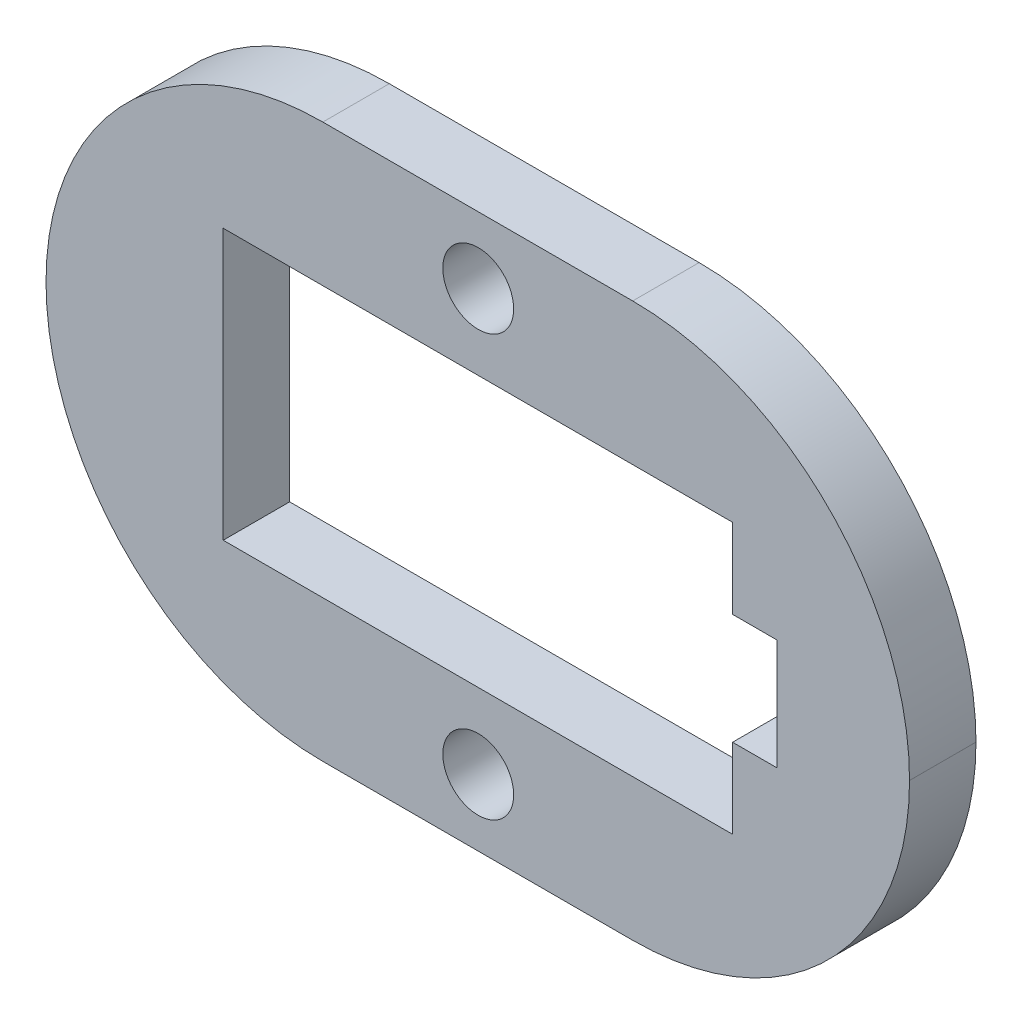
SolidWorks part; units mm, degrees
ref_plane "前视基准面" through (0, 0, 0) normal (0, 0, 1) x (1, 0, 0)
ref_plane "上视基准面" through (0, 0, 0) normal (0, 1, 0) x (1, 0, 0)
ref_plane "右视基准面" through (0, 0, 0) normal (1, 0, 0) x (0, 0, -1)
ref_plane "基准面4" through (0, 0, 0) normal (0, 0, -1) x (-1, 0, 0)
sketch "草图1" plane through (0, 0, 0) normal (0, 0, -1) x (-1, 0, 0)
  line L0 (-11.9978, 15) -> (-9.9969, 15)
  line L1 (-9.9969, 15) -> (-9.9969, 18.6)
  line L2 (-9.9969, 18.6) -> (13.0026, 18.6)
  line L3 (13.0026, 18.6) -> (13.0026, 6.4)
  line L4 (13.0026, 6.4) -> (-9.9969, 6.4)
  line L5 (-9.9969, 6.4) -> (-9.9969, 10.001)
  line L6 (-9.9969, 10.001) -> (-11.9978, 10.001)
  line L7 (-11.9978, 10.001) -> (-11.9978, 15)
  line L8 (8.5033, 25.001) -> (-5.4866, 25.001)
  line L9 (-17.9866, 12.501) -> (-17.9866, 12.5)
  line L10 (-5.4866, 0) -> (8.5033, 0)
  arc A0 (8.5033, 0) -> (21.0033, 12.5) centre (8.5033, 12.5) ccw
  arc A1 (21.0033, 12.5) -> (8.5033, 25.001) centre (8.5033, 12.501) ccw
  arc A2 (-5.4866, 25.001) -> (-17.9866, 12.501) centre (-5.4866, 12.501) ccw
  arc A3 (-17.9866, 12.5) -> (-5.4866, 0) centre (-5.4866, 12.5) ccw
  circle A4 centre (1.4879, 22.0005) radius 1.3
  circle A5 centre (1.4879, 2.9995) radius 1.3
extrude "凸台-拉伸1" add sketch "草图1" against normal blind 3
sketch "草图2" plane through (0, 0, 3) normal (0, 0, 1) x (1, 0, 0)
  circle A0 centre (-1.4879, 22.0005) radius 1.6
  circle A1 centre (-1.4879, 2.9995) radius 1.6
  dimension "D1" = 3.2
extrude "切除-拉伸1" cut sketch "草图2" against normal through all
